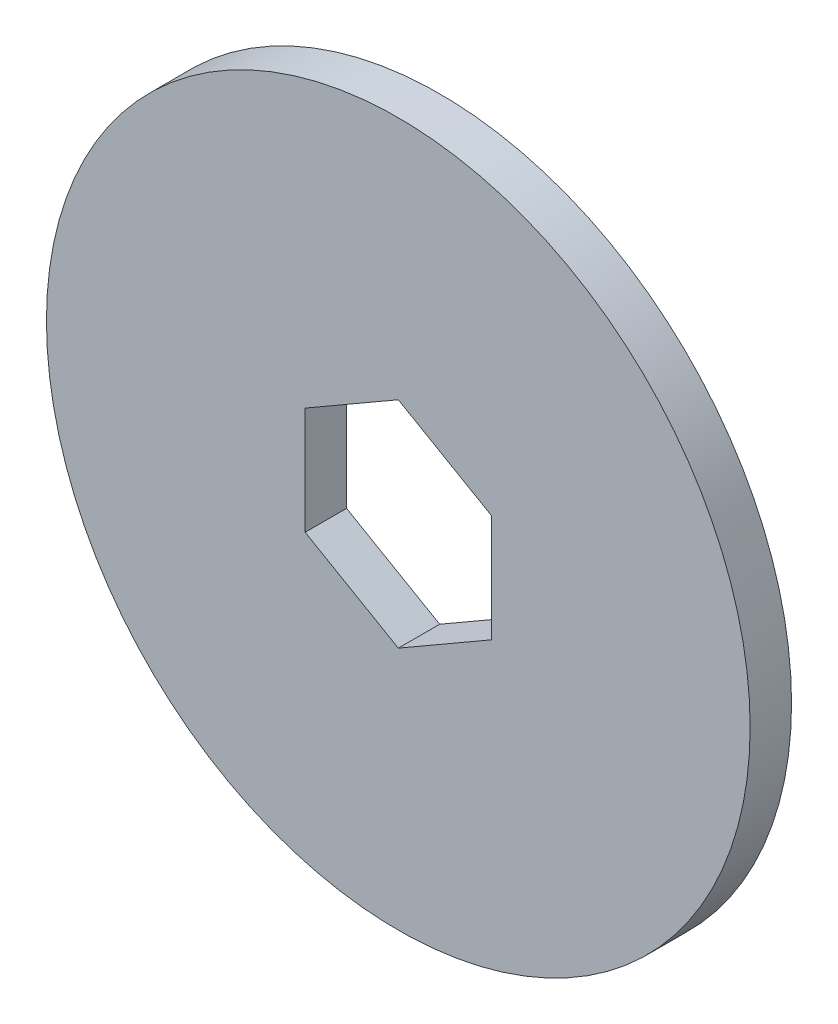
SolidWorks part; units mm, degrees
ref_plane "Front Plane" through (0, 0, 0) normal (0, 0, 1) x (1, 0, 0)
ref_plane "Top Plane" through (0, 0, 0) normal (0, 1, 0) x (1, 0, 0)
ref_plane "Right Plane" through (0, 0, 0) normal (1, 0, 0) x (0, 0, -1)
sketch "Model" plane through (0, 0, 0) normal (0, 0, 1) x (1, 0, 0)
  line L0 (628.8, -184.2058) -> (628.8, -199.7942)
  line L1 (628.8, -199.7942) -> (642.3, -207.5885)
  line L2 (642.3, -207.5885) -> (655.8, -199.7942)
  line L3 (655.8, -199.7942) -> (655.8, -184.2058)
  line L4 (655.8, -184.2058) -> (642.3, -176.4115)
  line L5 (642.3, -176.4115) -> (628.8, -184.2058)
  circle A0 centre (642.3, -192) radius 25
extrude "Boss-Extrude1" add sketch "Model" along normal blind 6
sketch "Sketch2" plane through (0, 0, 6) normal (0, 0, 1) x (1, 0, 0)
  circle A0 centre (642.3, -192) radius 25
  circle A1 centre (642.3, -192) radius 51
  circle M2 centre (642.3, -192) radius 25
extrude "Boss-Extrude2" add sketch "Sketch2" against normal blind 6 contours A1 M2
